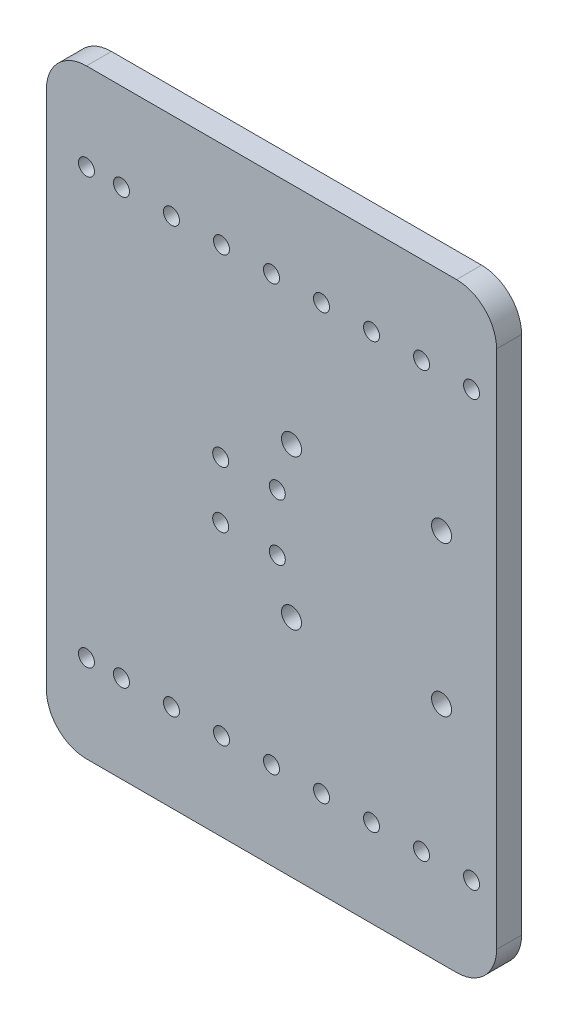
SolidWorks part; units mm, degrees
ref_plane "前视基准面" through (0, 0, 0) normal (0, 0, 1) x (1, 0, 0)
ref_plane "上视基准面" through (0, 0, 0) normal (0, 1, 0) x (1, 0, 0)
ref_plane "右视基准面" through (0, 0, 0) normal (1, 0, 0) x (0, 0, -1)
sketch "草图1" plane through (0, 0, 0) normal (0, 0, 1) x (1, 0, 0)
  line L1 (0, 0) -> (90, 0)
  line L2 (0, 0) -> (0, -120)
  line L3 (0, -120) -> (90, -120)
  line L4 (90, 0) -> (90, -120)
  circle A4 centre (79, -45) radius 2
  circle A5 centre (79, -75) radius 2
  circle A12 centre (49, -45) radius 2
  circle A13 centre (49, -75) radius 2
  circle A18 centre (85, -102.5) radius 1.6
  circle A19 centre (75, -102.5) radius 1.6
  circle A20 centre (65, -102.5) radius 1.6
  circle A21 centre (55, -102.5) radius 1.6
  circle A22 centre (45, -102.5) radius 1.6
  circle A23 centre (85, -17.5) radius 1.6
  circle A24 centre (75, -17.5) radius 1.6
  circle A25 centre (65, -17.5) radius 1.6
  circle A26 centre (55, -17.5) radius 1.6
  circle A27 centre (45, -17.5) radius 1.6
  circle A28 centre (35, -102.5) radius 1.6
  circle A29 centre (25, -102.5) radius 1.6
  circle A30 centre (15, -102.5) radius 1.6
  circle A31 centre (35, -17.5) radius 1.6
  circle A32 centre (25, -17.5) radius 1.6
  circle A33 centre (15, -17.5) radius 1.6
  circle A34 centre (8, -102.5) radius 1.6
  circle A35 centre (8, -17.5) radius 1.6
  dimension "D1" = 120
  dimension "D15" = 2
  dimension "D5" = 30
  dimension "D16" = 2
  dimension "D17" = 2
  dimension "D7" = 49
  dimension "D4" = 17.5
  dimension "D6" = 3.2
  dimension "D12" = 5
  dimension "D23" = 7
  dimension "D2" = 90
  dimension "D8" = 45
  dimension "D9" = 5
  dimension "D10" = 30
  dimension "D11" = 2
  dimension "D13" = 4
  dimension "D14" = 2
extrude "凸台-拉伸1" add sketch "草图1" along normal blind 5
fillet "圆角1" radius 8 4 edges at (0, -120, 2.5) (90, -120, 2.5) (90, 0, 2.5) (0, 0, 2.5)
sketch "内圈四孔_Ø3.2_PCD16" plane through (0, 0, 0) normal (0, 0, -1) x (-1, 0, 0)
  circle A15 centre (-46.1569, -54.3431) radius 1.6
  circle A16 centre (-34.8431, -54.3431) radius 1.6
  circle A17 centre (-34.8431, -65.6569) radius 1.6
  circle A18 centre (-46.1569, -65.6569) radius 1.6
extrude "内圈四孔_通孔_Ø3.2" cut sketch "内圈四孔_Ø3.2_PCD16" against normal blind 10
sketch "内圈沉孔_Ø6_PCD16" plane through (0, 0, 0) normal (0, 0, -1) x (-1, 0, 0)
  circle A10 centre (-46.1569, -54.3431) radius 3
  circle A11 centre (-34.8431, -54.3431) radius 3
  circle A12 centre (-34.8431, -65.6569) radius 3
  circle A13 centre (-46.1569, -65.6569) radius 3
extrude "内圈四孔_沉孔_Ø6深1" cut sketch "内圈沉孔_Ø6_PCD16" against normal blind 1
